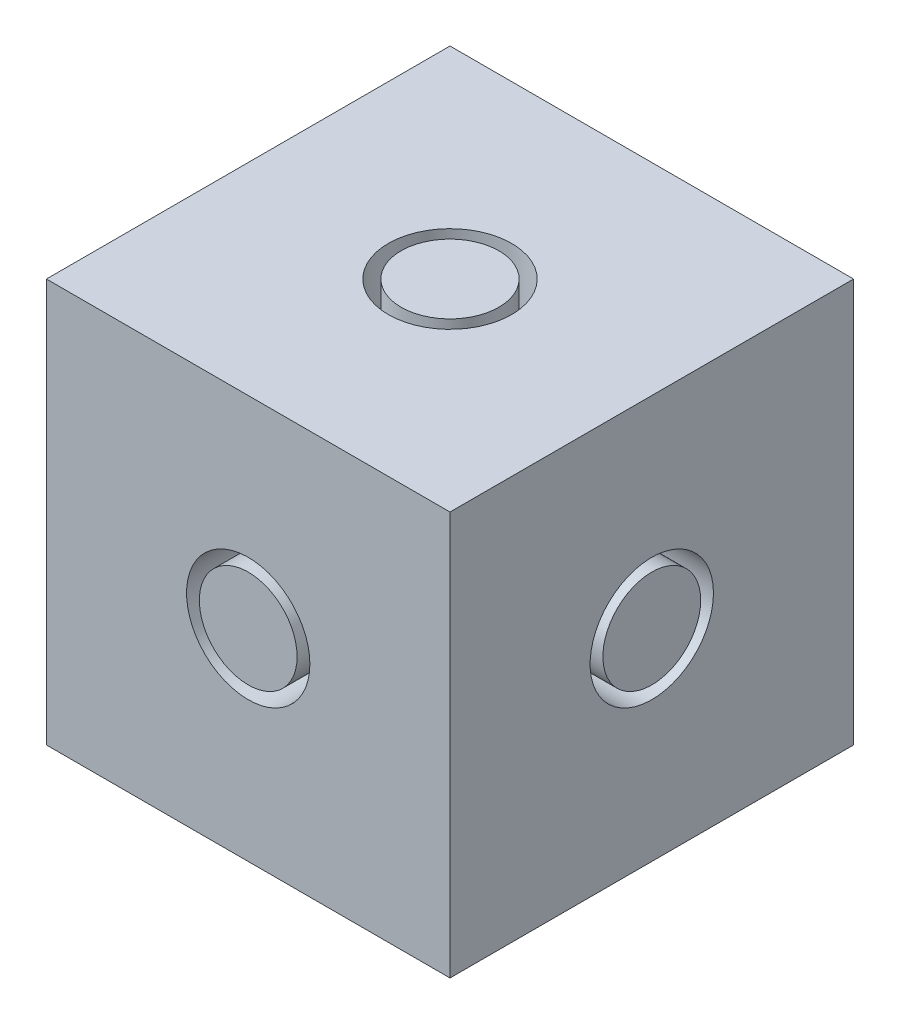
SolidWorks part; units mm, degrees
ref_plane "Front Plane" through (0, 0, 0) normal (0, 0, 1) x (1, 0, 0)
ref_plane "Top Plane" through (0, 0, 0) normal (0, 1, 0) x (1, 0, 0)
ref_plane "Right Plane" through (0, 0, 0) normal (1, 0, 0) x (0, 0, -1)
sketch "Sketch1" plane through (0, 0, 0) normal (0, 1, 0) x (1, 0, 0)
  line L1 (-27.65, 27.65) -> (27.65, 27.65)
  line L2 (-27.65, 27.65) -> (-27.65, -27.65)
  line L3 (-27.65, -27.65) -> (27.65, -27.65)
  line L4 (27.65, 27.65) -> (27.65, -27.65)
  point P0 (0, 0)
  dimension "D1" = 55.3
  dimension "D2" = 27.65
  dimension "D3" = 27.65
extrude "Boss-Extrude1" add sketch "Sketch1" along normal mid plane 55.3
sketch "Sketch2" plane through (0, 27.65, 0) normal (0, 1, 0) x (1, 0, 0)
  circle A0 centre (0, 0) radius 8.45
  circle A1 centre (0, 0) radius 6.7
  dimension "D1" = 16.9
  dimension "D2" = 13.4
extrude "Cut-Extrude2" cut sketch "Sketch2" against normal blind 9.5
sketch "Sketch3" plane through (0, -27.65, 0) normal (0, -1, 0) x (1, 0, 0)
  circle A0 centre (0, 0) radius 8.45
  circle A1 centre (0, 0) radius 6.7
  dimension "D1" = 16.9
  dimension "D2" = 13.4
extrude "Cut-Extrude3" cut sketch "Sketch3" against normal blind 9.5
sketch "Sketch4" plane through (27.65, 0, 0) normal (1, 0, 0) x (0, 0, -1)
  circle A0 centre (0, 0) radius 8.45
  circle A1 centre (0, 0) radius 6.7
  dimension "D1" = 16.9
  dimension "D2" = 13.4
extrude "Cut-Extrude4" cut sketch "Sketch4" against normal blind 9.5
sketch "Sketch5" plane through (-27.65, 0, 0) normal (-1, 0, 0) x (0, 0, 1)
  circle A0 centre (0, 0) radius 8.45
  circle A1 centre (0, 0) radius 6.7
  dimension "D1" = 16.9
  dimension "D2" = 13.4
extrude "Cut-Extrude5" cut sketch "Sketch5" against normal blind 9.5
sketch "Sketch6" plane through (0, 0, 27.65) normal (0, 0, 1) x (1, 0, 0)
  circle A0 centre (0, 0) radius 8.45
  circle A1 centre (0, 0) radius 6.7
  dimension "D1" = 16.9
  dimension "D2" = 13.4
extrude "Cut-Extrude6" cut sketch "Sketch6" against normal blind 9.5
sketch "Sketch7" plane through (0, 0, -27.65) normal (0, 0, -1) x (-1, 0, 0)
  circle A0 centre (0, 0) radius 8.45
  circle A1 centre (0, 0) radius 6.7
  dimension "D1" = 13.4
  dimension "D2" = 16.9
extrude "Cut-Extrude7" cut sketch "Sketch7" against normal blind 9.5
